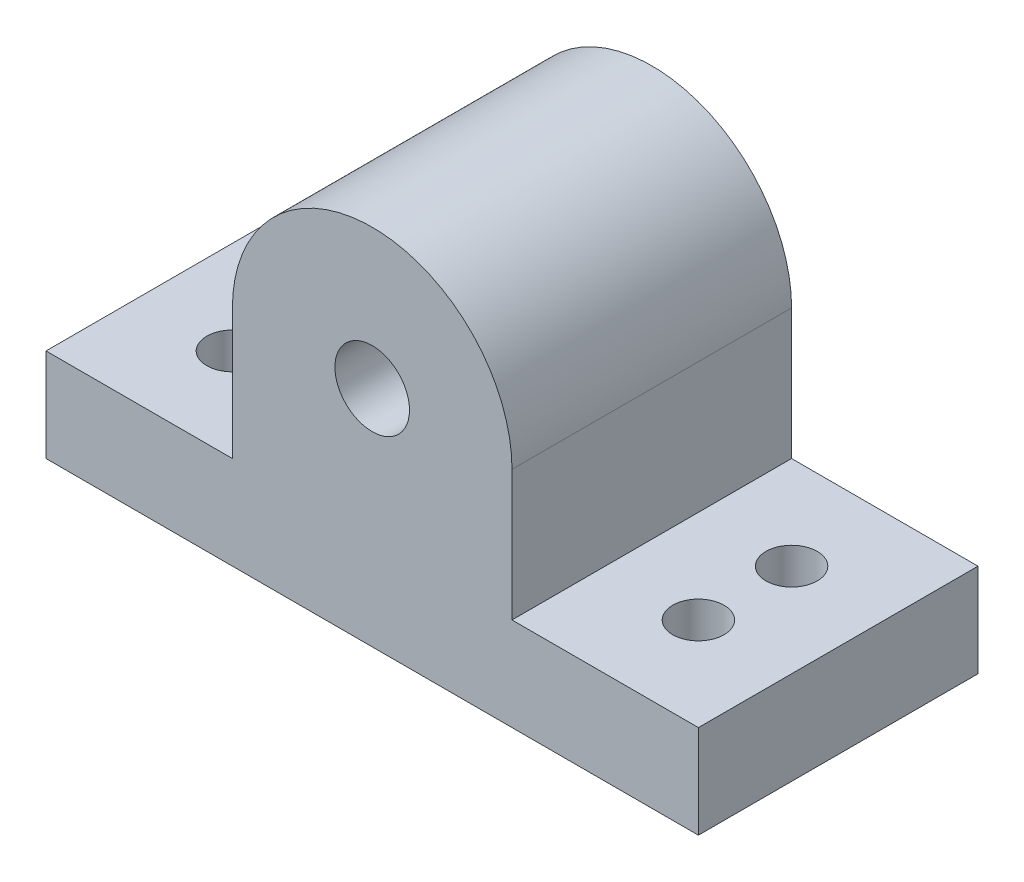
SolidWorks part; units mm, degrees
ref_plane "Front Plane" through (0, 0, 0) normal (0, 0, 1) x (1, 0, 0)
ref_plane "Top Plane" through (0, 0, 0) normal (0, 1, 0) x (1, 0, 0)
ref_plane "Right Plane" through (0, 0, 0) normal (1, 0, 0) x (0, 0, -1)
sketch "Sketch1" plane through (0, 0, 0) normal (0, 0, 1) x (1, 0, 0)
  line L0 (-13.9381, -41.7246) -> (-13.9381, -53.7246)
  line L1 (-13.9381, -53.7246) -> (1.0619, -53.7246)
  line L2 (1.0619, -53.7246) -> (1.0619, -41.7246)
  arc A0 (1.0619, -41.7246) -> (-13.9381, -41.7246) centre (-6.4381, -41.7246) ccw
  circle A1 centre (-6.4381, -41.7246) radius 2
  dimension "D1" = 15
  dimension "D3" = 4
  dimension "D2" = 12
extrude "Boss-Extrude1" add sketch "Sketch1" along normal blind 15
sketch "Sketch8" plane through (-13.9381, 0, 0) normal (-1, 0, 0) x (0, 0, 1)
  line L0 (15, -41.7246) -> (15, -53.7246) construction
  line L1 (0, -53.7246) -> (15, -53.7246)
  line L2 (0, -53.7246) -> (0, -48.7246)
  line L3 (0, -48.7246) -> (15, -48.7246)
  line L4 (15, -53.7246) -> (15, -48.7246)
  dimension "D1" = 5
sketch "Sketch9" plane through (1.0619, 0, 0) normal (1, 0, 0) x (0, 0, -1)
  line L0 (0, -53.7246) -> (0, -41.7246) construction
  line L1 (-15, -53.7246) -> (0, -53.7246)
  line L2 (-15, -53.7246) -> (-15, -48.7246)
  line L3 (-15, -48.7246) -> (0, -48.7246)
  line L4 (0, -53.7246) -> (0, -48.7246)
  dimension "D1" = 5
extrude "Boss-Extrude6" add sketch "Sketch8" along normal blind 10
extrude "Boss-Extrude7" add sketch "Sketch9" along normal blind 10
sketch "Sketch10" plane through (0, -48.7246, 0) normal (0, 1, 0) x (1, 0, 0)
  line L0 (11.0619, -15) -> (1.0619, -15) construction
  line L1 (11.0619, 0) -> (11.0619, -15) construction
  line L2 (11.0619, 0) -> (1.0619, 0) construction
  line L3 (-23.9381, -15) -> (-23.9381, 0) construction
  line L4 (-23.9381, 0) -> (-13.9381, 0) construction
  line L5 (-23.9381, -15) -> (-13.9381, -15) construction
  circle A0 centre (6.0619, -10) radius 1.375
  circle A1 centre (6.0619, -5) radius 1.375
  circle A2 centre (-18.9381, -10) radius 1.375
  circle A3 centre (-18.9381, -5) radius 1.375
  dimension "D1" = 5
  dimension "D2" = 5
  dimension "D3" = 5
  dimension "D4" = 5
  dimension "D5" = 5
  dimension "D6" = 5
  dimension "D7" = 5
  dimension "D8" = 5
  dimension "D9" = 2.75
  dimension "D10" = 2.75
  dimension "D11" = 2.75
  dimension "D12" = 2.75
extrude "Cut-Extrude1" cut sketch "Sketch10" against normal through all
